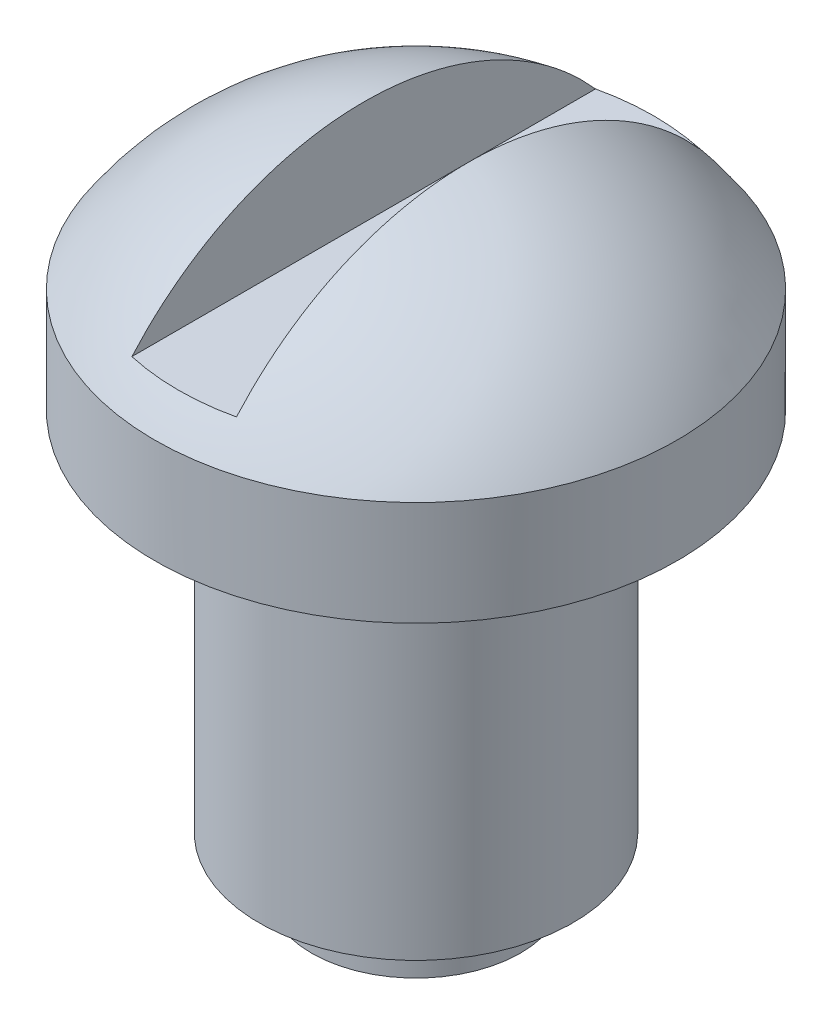
SolidWorks part; units mm, degrees
ref_plane "Front Plane" through (0, 0, 0) normal (0, 0, 1) x (1, 0, 0)
ref_plane "Top Plane" through (0, 0, 0) normal (0, 1, 0) x (1, 0, 0)
ref_plane "Right Plane" through (0, 0, 0) normal (1, 0, 0) x (0, 0, -1)
sketch "Sketch1" plane through (0, 0, 0) normal (0, 0, 1) x (1, 0, 0)
  line L0 (0, 10) -> (0, 12.6834)
  line L1 (0, 0) -> (2, 0)
  line L2 (0, 0) -> (0, 1)
  line L3 (0, 1) -> (2, 1)
  line L4 (2, 0) -> (2, 1)
  line L5 (0, 1) -> (3, 1)
  line L6 (0, 1) -> (0, 8)
  line L7 (0, 8) -> (3, 8)
  line L8 (3, 1) -> (3, 8)
  line L9 (0, 8) -> (5, 8)
  line L10 (0, 8) -> (0, 10)
  line L11 (0, 10) -> (5, 10)
  line L12 (5, 8) -> (5, 10)
  arc A0 (5, 10) -> (0, 12.6834) centre (0, 6.6834) ccw
  dimension "D7" = 6
  dimension "D1" = 2
  dimension "D2" = 1
  dimension "D3" = 7
  dimension "D4" = 3
  dimension "D5" = 5
  dimension "D6" = 2
revolve "Revolve1" add sketch "Sketch1" angle 360 about L10
sketch "Sketch2" plane through (0, 0, 0) normal (0, 0, 1) x (1, 0, 0)
  line L0 (5, 10) -> (-5, 10) construction
  line L1 (5, 10) -> (-5, 10)
  line L2 (0, 10) -> (0, 12.6834) construction
  line L3 (1, 10.5995) -> (-1, 10.5995)
  line L4 (-1, 10.5995) -> (-1, 12.5995)
  line L5 (1, 10.5995) -> (1, 12.5995)
  arc A0 (5, 10) -> (-5, 10) centre (0, 6.6834) ccw construction
  arc A1 (5, 10) -> (-5, 10) centre (0, 6.6834) ccw
  point P7 (0.5967, 12.6536)
  dimension "D1" = 2
  dimension "D2" = 2
extrude "Cut-Extrude1" cut sketch "Sketch2" against normal through all both and the other way through all contours L2 L3 L5 A1 | L3 L2 A1 L4
